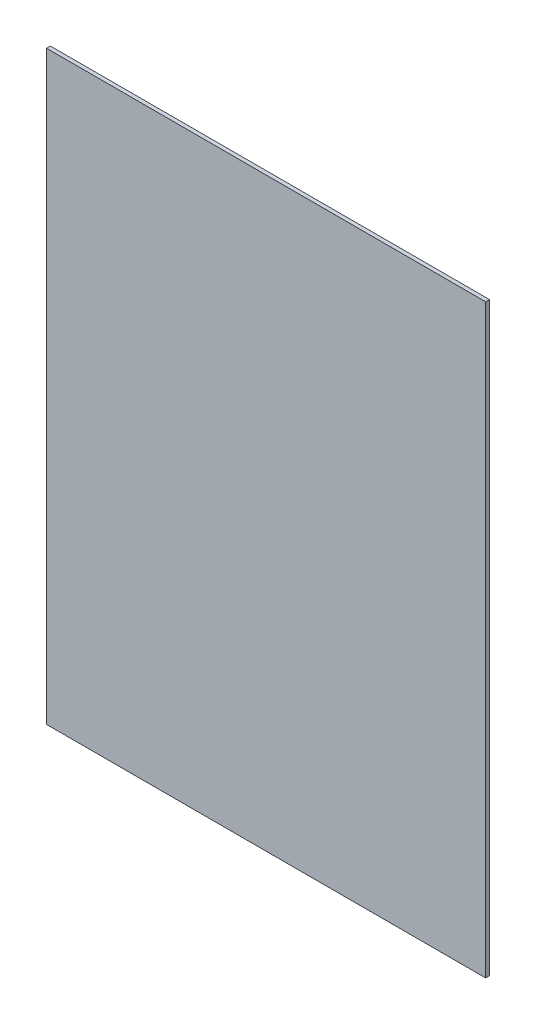
SolidWorks part; units mm, degrees
ref_plane "前视基准面" through (0, 0, 0) normal (0, 0, 1) x (1, 0, 0)
ref_plane "上视基准面" through (0, 0, 0) normal (0, 1, 0) x (1, 0, 0)
ref_plane "右视基准面" through (0, 0, 0) normal (1, 0, 0) x (0, 0, -1)
sketch "草图1" plane through (0, 0, 0) normal (0, 0, 1) x (1, 0, 0)
  line L1 (-750, 1000) -> (750, 1000)
  line L2 (-750, 1000) -> (-750, -1000)
  line L3 (-750, -1000) -> (750, -1000)
  line L4 (750, 1000) -> (750, -1000)
  line L5 (-750, 1000) -> (750, -1000) construction
  line L6 (-750, -1000) -> (750, 1000) construction
  point P0 (0, 0)
  dimension "D1" = 2000
  dimension "D2" = 1500
extrude "凸台-拉伸1" add sketch "草图1" along normal blind 13
